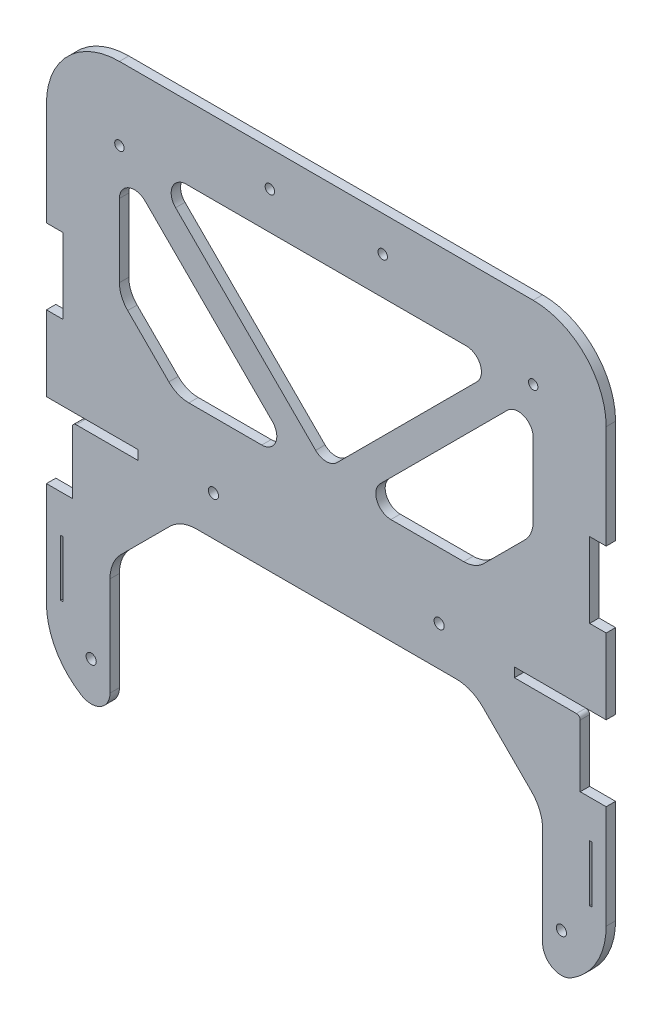
SolidWorks part; units mm, degrees
material "Thornel Mat VMA"
ref_plane "Front Plane" through (0, 0, 0) normal (0, 0, 1) x (1, 0, 0)
ref_plane "Top Plane" through (0, 0, 0) normal (0, 1, 0) x (1, 0, 0)
ref_plane "Right Plane" through (0, 0, 0) normal (1, 0, 0) x (0, 0, -1)
ref_plane "Plane1" through (0, 0, -196.85) normal (0, 0, 1) x (1, 0, 0)
sketch "Sketch1" plane through (0, 0, -196.85) normal (0, 0, 1) x (1, 0, 0)
  line L0 (46.4188, -88.9) -> (21.7892, -88.9)
  line L1 (18.1971, -80.2279) -> (61.1779, -37.2471)
  line L2 (69.85, -40.8392) -> (69.85, -65.4688)
  line L3 (-3.5921, -81.3625) -> (-50.8825, -34.0721)
  line L4 (-47.2904, -25.4) -> (47.2904, -25.4)
  line L5 (50.8825, -34.0721) -> (3.5921, -81.3625)
  line L6 (-94.488, -136.525) -> (-94.488, -171.45)
  line L7 (-69.85, -196.088) -> (69.85, -196.088)
  line L8 (94.488, -171.45) -> (94.488, -136.525)
  line L9 (94.488, -136.525) -> (85.725, -136.525)
  line L10 (85.725, -136.525) -> (85.725, -115.57)
  line L11 (84.455, -114.3) -> (63.5, -114.3)
  line L12 (63.5, -114.3) -> (63.5, -111.125)
  line L13 (63.5, -111.125) -> (94.488, -111.125)
  line L14 (94.488, -111.125) -> (94.488, -85.725)
  line L15 (94.488, -85.725) -> (88.9, -85.725)
  line L16 (88.9, -85.725) -> (88.9, -60.325)
  line L17 (88.9, -60.325) -> (94.488, -60.325)
  line L18 (94.488, -60.325) -> (94.488, -25.4)
  line L19 (69.85, -0.762) -> (-69.85, -0.762)
  line L20 (-94.488, -25.4) -> (-94.488, -60.325)
  line L21 (-94.488, -60.325) -> (-88.9, -60.325)
  line L22 (-88.9, -60.325) -> (-88.9, -85.725)
  line L23 (-88.9, -85.725) -> (-94.488, -85.725)
  line L24 (-94.488, -85.725) -> (-94.488, -111.125)
  line L25 (-94.488, -111.125) -> (-63.5, -111.125)
  line L26 (-63.5, -111.125) -> (-63.5, -114.3)
  line L27 (-63.5, -114.3) -> (-84.455, -114.3)
  line L28 (-85.725, -115.57) -> (-85.725, -136.525)
  line L29 (-85.725, -136.525) -> (-94.488, -136.525)
  line L30 (-69.85, -65.4688) -> (-69.85, -40.8392)
  line L31 (-61.1779, -37.2471) -> (-18.1971, -80.2279)
  line L32 (-21.7892, -88.9) -> (-46.4188, -88.9)
  line L33 (0, 0) -> (0, -50000) construction
  line L34 (-67.0602, -72.204) -> (-53.154, -86.1102)
  line L35 (-19.05, -130.831) -> (19.05, -130.831) construction
  line L36 (-19.05, -130.831) -> (-19.05, -159.406) construction
  line L37 (-19.05, -159.406) -> (19.05, -159.406) construction
  line L38 (19.05, -130.831) -> (19.05, -159.406) construction
  line L39 (-61.1779, -139.7) -> (73.825, -139.7) construction
  line L40 (-61.1779, -139.7) -> (-61.1779, -25.8853) construction
  line L41 (-61.1779, -25.8853) -> (73.825, -25.8853) construction
  line L42 (73.825, -139.7) -> (73.825, -25.8853) construction
  line L43 (67.0602, -72.204) -> (53.154, -86.1102)
  line L44 (88.9, -149.225) -> (88.9, -168.275)
  line L45 (-89.6937, -149.225) -> (-88.9, -149.225)
  line L46 (-89.6937, -149.225) -> (-89.6937, -168.275)
  line L47 (-89.6937, -168.275) -> (-88.9, -168.275)
  line L48 (-88.9, -149.225) -> (-88.9, -168.275)
  line L49 (89.6937, -168.275) -> (88.9, -168.275)
  line L50 (89.6938, -149.225) -> (89.6937, -168.275)
  line L51 (89.6938, -149.225) -> (88.9, -149.225)
  line L52 (-50.8, -196.088) -> (-50.8, -192.913)
  line L53 (-50.8, -192.913) -> (-25.4, -192.913)
  line L54 (-25.4, -192.913) -> (-25.4, -196.088)
  line L55 (-69.85, -169.8625) -> (-60.325, -169.8625)
  line L56 (-69.85, -173.0375) -> (-60.325, -173.0375)
  line L57 (50.8, -196.088) -> (50.8, -192.913)
  line L58 (25.4, -192.913) -> (25.4, -196.088)
  line L59 (50.8, -192.913) -> (25.4, -192.913)
  line L60 (-63.5, -111.125) -> (63.5, -111.125) construction
  line L61 (73.025, -196.088) -> (73.025, -153.6668)
  line L62 (69.3053, -144.6866) -> (52.8194, -128.2007)
  line L63 (43.8392, -124.481) -> (-43.8392, -124.481)
  line L64 (-69.3053, -144.6866) -> (-52.8194, -128.2007)
  line L65 (-73.025, -196.088) -> (-73.025, -153.6668)
  circle A0 centre (-19.05, -12.7) radius 1.5875
  circle A1 centre (19.05, -12.7) radius 1.5875
  circle A2 centre (-69.85, -25.4) radius 1.5875
  circle A3 centre (69.85, -25.4) radius 1.5875
  circle A4 centre (-69.85, -171.45) radius 1.5875
  circle A5 centre (69.85, -171.45) radius 1.5875
  arc A6 (69.85, -65.4688) -> (67.0602, -72.204) centre (60.325, -65.4688) cw
  arc A7 (21.7892, -88.9) -> (18.1971, -80.2279) centre (21.7892, -83.82) cw
  arc A8 (61.1779, -37.2471) -> (69.85, -40.8392) centre (64.77, -40.8392) cw
  circle A9 centre (-83.82, -84.8367) radius 1.5875
  arc A10 (3.5921, -81.3625) -> (-3.5921, -81.3625) centre (0, -77.7704) cw
  arc A11 (-50.8825, -34.0721) -> (-47.2904, -25.4) centre (-47.2904, -30.48) cw
  arc A12 (47.2904, -25.4) -> (50.8825, -34.0721) centre (47.2904, -30.48) cw
  arc A13 (-94.488, -171.45) -> (-69.85, -196.088) centre (-69.85, -171.45) ccw
  arc A14 (69.85, -196.088) -> (94.488, -171.45) centre (69.85, -171.45) ccw
  arc A15 (94.488, -25.4) -> (69.85, -0.762) centre (69.85, -25.4) ccw
  arc A16 (-69.85, -0.762) -> (-94.488, -25.4) centre (-69.85, -25.4) ccw
  arc A17 (-69.85, -40.8392) -> (-61.1779, -37.2471) centre (-64.77, -40.8392) cw
  arc A18 (-18.1971, -80.2279) -> (-21.7892, -88.9) centre (-21.7892, -83.82) cw
  arc A19 (46.4188, -88.9) -> (53.154, -86.1102) centre (46.4188, -79.375) ccw
  arc A20 (85.725, -115.57) -> (84.455, -114.3) centre (84.455, -115.57) ccw
  arc A21 (-84.455, -114.3) -> (-85.725, -115.57) centre (-84.455, -115.57) ccw
  circle A22 centre (-19.05, -130.831) radius 1.5875
  circle A23 centre (19.05, -130.831) radius 1.5875
  circle A24 centre (19.05, -159.406) radius 1.5875
  circle A25 centre (-19.05, -159.406) radius 1.5875
  arc A26 (-46.4188, -88.9) -> (-53.154, -86.1102) centre (-46.4188, -79.375) cw
  arc A27 (-69.85, -65.4688) -> (-67.0602, -72.204) centre (-60.325, -65.4688) ccw
  circle A28 centre (-60.325, -171.45) radius 1.5875
  circle A29 centre (-79.375, -180.213) radius 1.7145
  circle A30 centre (38.1, -111.125) radius 1.7145
  circle A31 centre (79.375, -180.213) radius 1.7145
  circle A32 centre (-38.1, -111.125) radius 1.7145
  arc A33 (73.025, -153.6668) -> (69.3053, -144.6866) centre (60.325, -153.6668) ccw
  arc A34 (52.8194, -128.2007) -> (43.8392, -124.481) centre (43.8392, -137.181) ccw
  arc A35 (-52.8194, -128.2007) -> (-43.8392, -124.481) centre (-43.8392, -137.181) cw
  arc A36 (-73.025, -153.6668) -> (-69.3053, -144.6866) centre (-60.325, -153.6668) cw
  arc A37 (73.025, -187.0617) -> (82.6823, -192.4824) centre (79.375, -187.0617) ccw
  arc A38 (-73.025, -187.0617) -> (-82.6823, -192.4824) centre (-79.375, -187.0617) cw
  point P84 (0, -130.831)
  point P95 (-69.85, -69.4142)
  point P135 (0, -124.481)
  dimension "D1" = 1.27
  dimension "D4" = 3.175
  dimension "D7" = 3.175
  dimension "D11" = 9.525
  dimension "D20" = 3.429
  dimension "D24" = 12.7
  dimension "D29" = 6.35
  dimension "D2" = 38.1
  dimension "D3" = 28.575
  dimension "D5" = 56.388
  dimension "D6" = 19.706
  dimension "D8" = 9.525
  dimension "D9" = 9.525
  dimension "D10" = 28.575
  dimension "D12" = 0.7937
  dimension "D13" = 19.05
  dimension "D14" = 12.7
  dimension "D15" = 3.175
  dimension "D16" = 3.175
  dimension "D17" = 25.4
  dimension "D18" = 25.4
  dimension "D19" = 9.525
  dimension "D21" = 76.2
  dimension "D22" = 158.75
  dimension "D23" = 15.875
  dimension "D25" = 6.35
  dimension "D26" = 45
  dimension "D27" = 146.05
  dimension "D28" = 41.275
extrude "Boss-Extrude1" add sketch "Sketch1" against normal blind 3.175 contours L27 A21 L28 L29 L6 A13 L7 L52 L53 L54 L58 L59 L57 A14 L8 L9 L10 A20 L11 L12 L13 L14 L15 L16 L17 L18 A15 L19 A16 L20 L21 L22 L23 L24 L25 L26 A28 L56 A4 L55 A27 L30 A17 L31 A18 L32 A26 | A9
